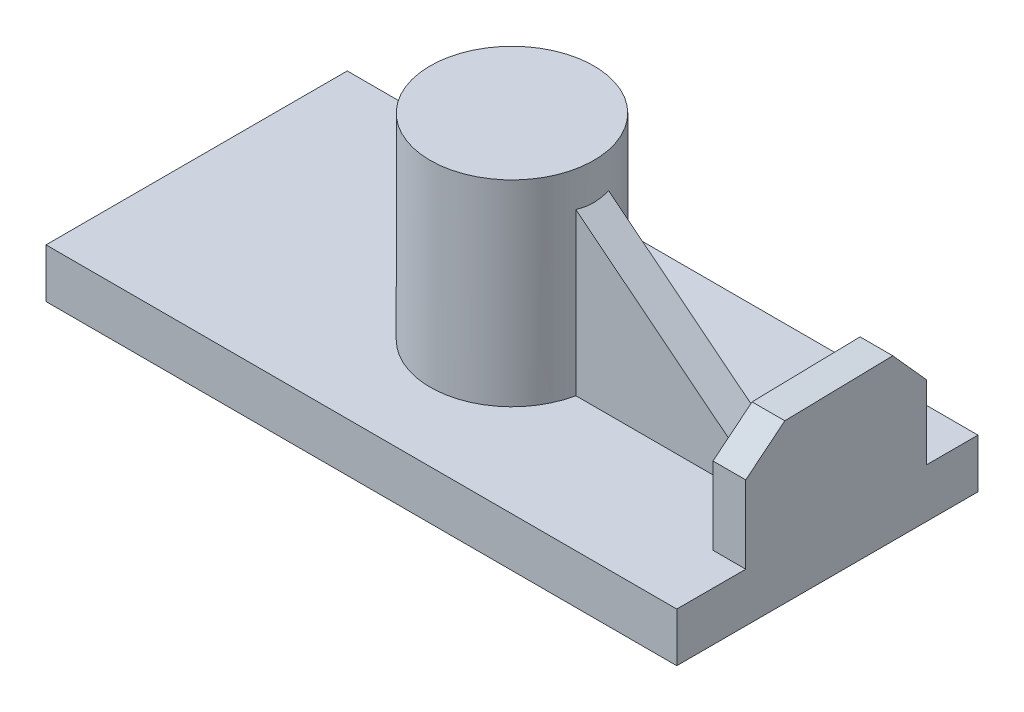
SolidWorks part; units mm, degrees
ref_plane "Plan de face" through (0, 0, 0) normal (0, 0, 1) x (1, 0, 0)
ref_plane "Plan de dessus" through (0, 0, 0) normal (0, 1, 0) x (1, 0, 0)
ref_plane "Plan de droite" through (0, 0, 0) normal (1, 0, 0) x (0, 0, -1)
sketch "Esquisse1" plane through (0, 0, 0) normal (0, 1, 0) x (1, 0, 0)
  line L1 (-96.3076, -45.9944) -> (96.3076, -45.9944)
  line L2 (-96.3076, -45.9944) -> (-96.3076, 45.9944)
  line L3 (-96.3076, 45.9944) -> (96.3076, 45.9944)
  line L4 (96.3076, -45.9944) -> (96.3076, 45.9944)
  line L5 (-96.3076, -45.9944) -> (96.3076, 45.9944) construction
  line L6 (-96.3076, 45.9944) -> (96.3076, -45.9944) construction
  point P0 (0, 0)
extrude "Boss.-Extru.1" add sketch "Esquisse1" along normal blind 15
sketch "Esquisse3" plane through (0, 15, 0) normal (0, 1, 0) x (1, 0, 0)
  circle A0 centre (0, 0) radius 25
extrude "Boss.-Extru.2" add sketch "Esquisse3" along normal blind 60
sketch "Esquisse4" plane through (96.3076, 0, 0) normal (1, 0, 0) x (0, 0, -1)
  line L0 (-45.9944, 15) -> (45.9944, 15) construction
  line L1 (-24.9307, 15) -> (30.2241, 15)
  line L2 (-24.9307, 15) -> (-24.9307, 38.6178)
  line L4 (30.2241, 15) -> (30.2241, 37.5509)
  line L5 (30.2241, 37.5509) -> (19.9796, 48.9901)
  line L6 (19.9796, 48.9901) -> (-12.997, 48.2819)
  line L7 (-12.997, 48.2819) -> (-24.9307, 38.6178)
extrude "Boss.-Extru.3" add sketch "Esquisse4" against normal blind 10
sketch "Esquisse5" plane through (0, 0, 0) normal (0, 0, 1) x (1, 0, 0)
  line L0 (25.4723, 63.4685) -> (86.3076, 15)
  line L1 (-96.3076, 15) -> (96.3076, 15) construction
  point P4 (87.3315, 15)
  point P5 (0, 0)
  point P6 (84.0254, 15)
  point P7 (86.3076, 15)
rib "Nervure1" sketch "Esquisse5" sketch "Esquisse5" thickness 10 extrusion direction parallel to sketch draft on no parameters "D1"=10
